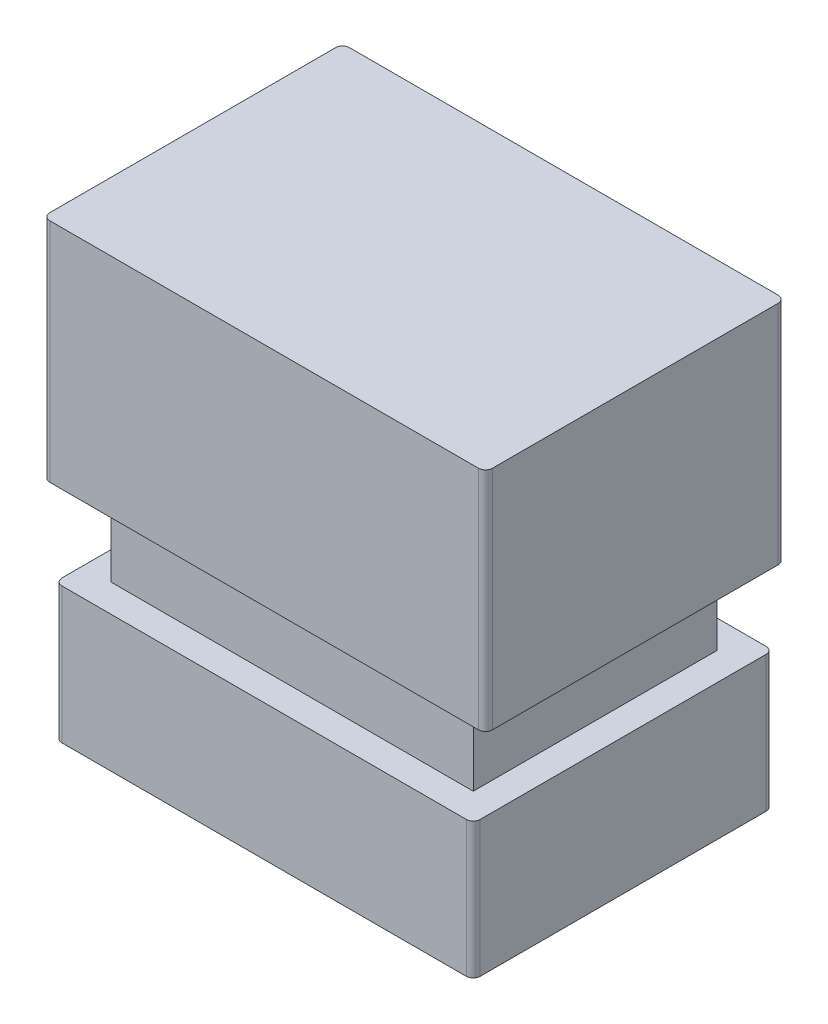
SolidWorks part; units mm, degrees
ref_plane "前基準面" through (0, 0, 0) normal (0, 0, 1) x (1, 0, 0)
ref_plane "上基準面" through (0, 0, 0) normal (0, 1, 0) x (1, 0, 0)
ref_plane "右基準面" through (0, 0, 0) normal (1, 0, 0) x (0, 0, -1)
sketch "草圖1" plane through (0, 0, 0) normal (0, 1, 0) x (1, 0, 0)
  line L1 (-300, 215) -> (300, 215)
  line L2 (-300, 215) -> (-300, -215)
  line L3 (-300, -215) -> (300, -215)
  line L4 (300, 215) -> (300, -215)
  line L5 (-300, 215) -> (300, -215) construction
  line L6 (-300, -215) -> (300, 215) construction
  point P0 (0, 0)
extrude "填料-伸長1" add sketch "草圖1" along normal blind 195
sketch "草圖2" plane through (0, 195, 0) normal (0, 1, 0) x (1, 0, 0)
  line L1 (-260, 175) -> (260, 175)
  line L2 (-260, 175) -> (-260, -175)
  line L3 (-260, -175) -> (260, -175)
  line L4 (260, 175) -> (260, -175)
  line L5 (-260, 175) -> (260, -175) construction
  line L6 (-260, -175) -> (260, 175) construction
  point P0 (0, 0)
extrude "填料-伸長2" add sketch "草圖2" along normal blind 120
sketch "草圖3" plane through (0, 315, 0) normal (0, 1, 0) x (1, 0, 0)
  line L1 (-317.5, 215) -> (317.5, 215)
  line L2 (-317.5, 215) -> (-317.5, -215)
  line L3 (-317.5, -215) -> (317.5, -215)
  line L4 (317.5, 215) -> (317.5, -215)
  line L5 (-317.5, 215) -> (317.5, -215) construction
  line L6 (-317.5, -215) -> (317.5, 215) construction
  point P0 (0, 0)
extrude "填料-伸長3" add sketch "草圖3" along normal blind 325
fillet "圓角2" radius 10 4 edges at (-317.5, 477.5, -215) (317.5, 477.5, -215) (317.5, 477.5, 215) (-317.5, 477.5, 215)
fillet "圓角3" radius 10 4 edges at (-300, 97.5, -215) (300, 97.5, -215) (300, 97.5, 215) (-300, 97.5, 215)
